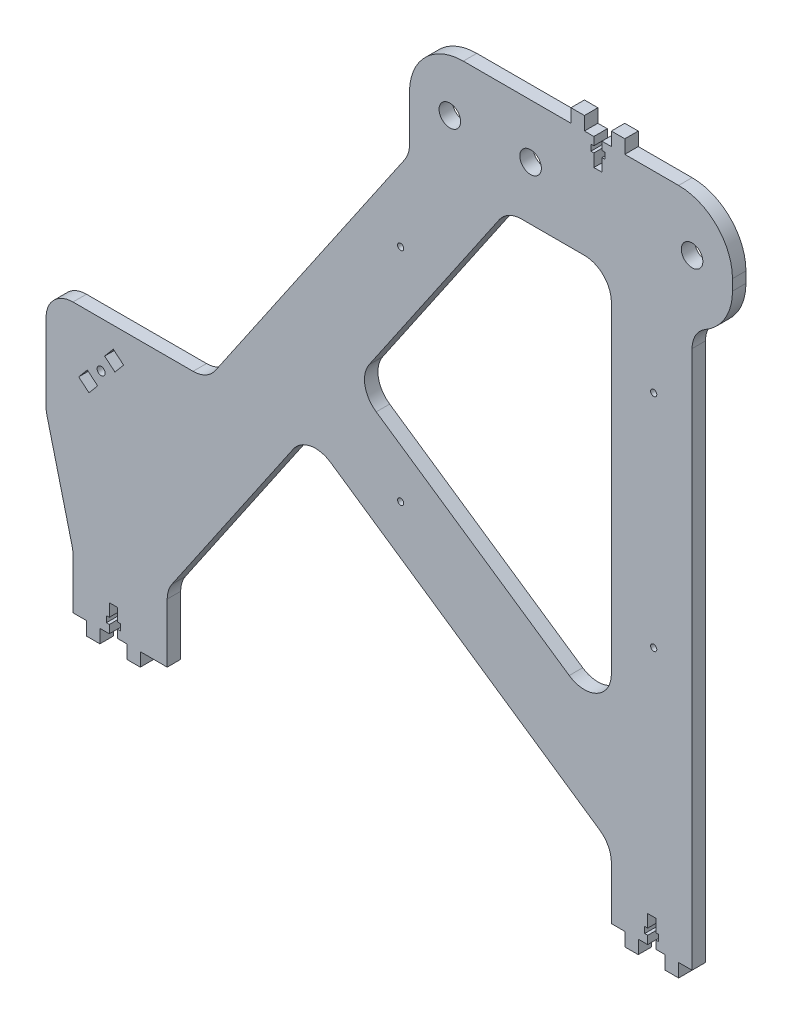
SolidWorks part; units mm, degrees
ref_plane "Plan de face" through (0, 0, 0) normal (0, 0, 1) x (1, 0, 0)
ref_plane "Plan de dessus" through (0, 0, 0) normal (0, 1, 0) x (1, 0, 0)
ref_plane "Plan de droite" through (0, 0, 0) normal (1, 0, 0) x (0, 0, -1)
sketch "Esquisse1" plane through (0, 0, 0) normal (0, 0, 1) x (1, 0, 0)
  line L0 (0, 0) -> (0, 38.8315) construction
  line L1 (-35, 0) -> (220.1536, 0) construction
  line L2 (-20, 0) -> (-20, 33.6786) construction
  line L3 (-21.5, 0) -> (-25, 0)
  line L4 (-25, -5) -> (-30, -5)
  line L5 (-30, -5) -> (-30, 0)
  line L6 (-25, -5) -> (-25, 0)
  line L7 (-18.5, 0) -> (-15, 0)
  line L8 (-15, 0) -> (-15, -5)
  line L9 (-15, -5) -> (-10, -5)
  line L10 (-10, -5) -> (-10, 0)
  line L11 (-21.5, 0) -> (-18.5, 0) construction
  line L12 (-18.5, 0) -> (-18.5, 3)
  line L13 (-18.5, 5.3) -> (-17.4, 5.3)
  line L14 (-22.6, 3) -> (-22.6, 5.3)
  line L15 (-17.4, 3) -> (-18.5, 3)
  line L16 (-18.5, 5.3) -> (-18.5, 10)
  line L17 (-18.5, 10) -> (-21.5, 10)
  line L18 (-21.5, 10) -> (-21.5, 5.3)
  line L19 (-21.5, 3) -> (-22.6, 3)
  line L20 (-17.4, 5.3) -> (-17.4, 3)
  line L21 (-22.6, 5.3) -> (-21.5, 5.3)
  line L22 (-21.5, 3) -> (-21.5, 0)
  line L23 (-20, 10) -> (-20, 0) construction
  line L45 (0, 0) -> (0, 95.9934) construction
  line L47 (-35, 95.9934) -> (-35, 0) construction
  line L48 (-35, 0) -> (-30, 0)
  line L52 (0, 20) -> (-35, 20) construction
  line L55 (-35, 20) -> (-57.9813, 39.2836) construction
  line L56 (-57.9813, 39.2836) -> (9.2875, 119.4515) construction
  line L57 (-35, 20) -> (-54.2836, 42.9813) construction
  line L58 (-54.2836, 42.9813) -> (25.8842, 110.2501) construction
  line L59 (-35, 20) -> (-50, 45.9808) construction
  line L60 (-50, 45.9808) -> (40.631, 98.3066) construction
  line L61 (-35, 20) -> (-45.2606, 48.1908) construction
  line L62 (-45.2606, 48.1908) -> (53.0798, 83.9838) construction
  line L63 (-45, 100) -> (14.8866, 100)
  line L65 (-45, 100) -> (-45, 60)
  line L66 (-45, 60) -> (-35, 20)
  line L67 (-35, 20) -> (-35, 0)
  line L68 (117.314, 250) -> (14.8866, 100) construction
  line L71 (86.7293, 178.6106) -> (180.7293, 178.6106) construction
  line L72 (117.314, 250) -> (210, 250) construction
  line L73 (210, 250) -> (210, 210)
  line L75 (135, 230) -> (210, 230) construction
  line L77 (14.8866, 100) -> (90, 210)
  line L79 (90, 210) -> (90, 250)
  line L80 (90, 250) -> (117.314, 250)
  line L81 (135, 230) -> (105, 230) construction
  line L82 (170, 250) -> (210, 250)
  line L83 (150, 250) -> (117.314, 250)
  line L84 (160, 250) -> (160, 238.7792) construction
  line L85 (161.5, 250) -> (165, 250)
  line L86 (165, 255) -> (170, 255)
  line L87 (170, 255) -> (170, 250)
  line L88 (165, 255) -> (165, 250)
  line L89 (158.5, 250) -> (155, 250)
  line L90 (155, 250) -> (155, 255)
  line L91 (155, 255) -> (150, 255)
  line L92 (150, 255) -> (150, 250)
  line L93 (161.5, 250) -> (158.5, 250) construction
  line L94 (158.5, 250) -> (158.5, 247)
  line L95 (158.5, 244.7) -> (157.4, 244.7)
  line L96 (162.6, 247) -> (162.6, 244.7)
  line L97 (157.4, 247) -> (158.5, 247)
  line L98 (158.5, 244.7) -> (158.5, 240)
  line L99 (158.5, 240) -> (161.5, 240)
  line L100 (161.5, 240) -> (161.5, 244.7)
  line L101 (161.5, 247) -> (162.6, 247)
  line L102 (157.4, 244.7) -> (157.4, 247)
  line L103 (162.6, 244.7) -> (161.5, 244.7)
  line L104 (161.5, 247) -> (161.5, 250)
  line L105 (160, 240) -> (160, 250) construction
  line L106 (-10, 0) -> (0, 0)
  line L107 (190, 0) -> (195, 0)
  line L108 (195, 0) -> (195, 210)
  line L109 (195, 210) -> (210, 210)
  line L110 (170, 0) -> (165, 0)
  line L112 (180, 0) -> (180, 11.2208) construction
  line L113 (178.5, 0) -> (175, 0)
  line L114 (175, -5) -> (170, -5)
  line L115 (170, -5) -> (170, 0)
  line L116 (175, -5) -> (175, 0)
  line L117 (181.5, 0) -> (185, 0)
  line L118 (185, 0) -> (185, -5)
  line L119 (185, -5) -> (190, -5)
  line L120 (190, -5) -> (190, 0)
  line L121 (178.5, 0) -> (181.5, 0) construction
  line L122 (181.5, 0) -> (181.5, 3)
  line L123 (181.5, 5.3) -> (182.6, 5.3)
  line L124 (177.4, 3) -> (177.4, 5.3)
  line L125 (182.6, 3) -> (181.5, 3)
  line L126 (181.5, 5.3) -> (181.5, 10)
  line L127 (181.5, 10) -> (178.5, 10)
  line L128 (178.5, 10) -> (178.5, 5.3)
  line L129 (178.5, 3) -> (177.4, 3)
  line L130 (182.6, 5.3) -> (182.6, 3)
  line L131 (177.4, 5.3) -> (178.5, 5.3)
  line L132 (178.5, 3) -> (178.5, 0)
  line L133 (180, 10) -> (180, 0) construction
  line L134 (165, 0) -> (165, 210) construction
  line L135 (165, 210) -> (126.327, 210)
  line L136 (126.327, 210) -> (0, 25) construction
  line L137 (0, 25) -> (0, 0)
  line L138 (180.7293, 178.6106) -> (180.7293, 96.6106) construction
  line L139 (180.7293, 96.6106) -> (86.7293, 96.6106) construction
  line L140 (86.7293, 96.6106) -> (86.7293, 178.6106) construction
  line L141 (0, 25) -> (52.4705, 101.8406)
  line L142 (52.4705, 101.8406) -> (165, 25)
  line L143 (165, 25) -> (165, 0)
  line L144 (69.3881, 126.6156) -> (165, 61.327)
  line L145 (165, 61.327) -> (165, 210)
  line L146 (126.327, 210) -> (69.3881, 126.6156)
  line L147 (66.4529, 175.5164) -> (91.2278, 158.5988) construction
  line L148 (78.8404, 167.0576) -> (37.9736, 107.2102) construction
  line L149 (64.949, 93.3197) -> (81.8665, 118.0947) construction
  line L150 (73.4078, 105.7072) -> (48.5418, 122.6869) construction
  circle A7 centre (135, 230) radius 4
  circle A8 centre (195, 230) radius 4
  circle A9 centre (105, 230) radius 4
  circle A10 centre (86.7293, 178.6106) radius 1.15
  circle A11 centre (180.7293, 96.6106) radius 1.15
  circle A12 centre (86.7293, 96.6106) radius 1.15
  circle A13 centre (180.7293, 178.6106) radius 1.15
  point P68 (-35, 20)
  point P86 (90, 230)
  line B0 (-29.6722, 80.7998) -> (-32.8861, 76.9696)
  line B1 (-29.6722, 80.7998) -> (-25.842, 77.5859)
  line B2 (-25.842, 77.5859) -> (-29.0559, 73.7556)
  line B3 (-32.8861, 76.9696) -> (-29.0559, 73.7556)
  line B4 (-23.2443, 88.4602) -> (-20.0304, 92.2905)
  line B5 (-23.2443, 88.4602) -> (-19.4141, 85.2463)
  line B6 (-19.4141, 85.2463) -> (-16.2001, 89.0765)
  line B7 (-20.0304, 92.2905) -> (-16.2001, 89.0765)
  line B8 (-24.5431, 83.023) -> (-29.8843, 87.5048) construction
  circle B9 centre (-24.5431, 83.023) radius 1.5
  dimension "D14" = 100
  dimension "D25" = 8
  dimension "D52" = 2.3
  dimension "D1" = 20
  dimension "D2" = 10
  dimension "D3" = 5
  dimension "D4" = 5
  dimension "D5" = 5.2
  dimension "D6" = 3
  dimension "D7" = 2.3
  dimension "D8" = 3
  dimension "D9" = 10
  dimension "D10" = 5
  dimension "D11" = 200
  dimension "D12" = 10
  dimension "D13" = 20
  dimension "D15" = 15
  dimension "D16" = 30
  dimension "D17" = 50
  dimension "D18" = 55
  dimension "D20" = 10
  dimension "D21" = 40
  dimension "D22" = 230
  dimension "D23" = 5
  dimension "D24" = 30
  dimension "D26" = 60
  dimension "D27" = 15
  dimension "D28" = 40
  dimension "D29" = 30
  dimension "D30" = 15
  dimension "D31" = 25
  dimension "D32" = 10
  dimension "D33" = 5
  dimension "D34" = 5
  dimension "D35" = 5.2
  dimension "D36" = 3
  dimension "D37" = 2.3
  dimension "D38" = 3
  dimension "D39" = 10
  dimension "D40" = 10
  dimension "D41" = 5
  dimension "D42" = 5
  dimension "D43" = 5.2
  dimension "D44" = 3
  dimension "D45" = 2.3
  dimension "D46" = 3
  dimension "D47" = 10
  dimension "D48" = 30
  dimension "D49" = 25
  dimension "D50" = 94
  dimension "D51" = 82
  dimension "D19" = 4
sketch_block_instance "Trou M3 plots 5mm-1"
sketch_block "Trou M3 plots 5mm" parameters "D2"=3, "D1"=5, "D3"=5, "D4"=10
sketch_block_instance "Trou M3 plots 5mm-6"
sketch_block_instance "Trou M3 plots 5mm-7"
sketch_block_instance "Trou M3 plots 5mm-8"
extrude "Boss.-Extru.1" add sketch "Esquisse1" along normal blind 5
fillet "Congé1" radius 10 13 edges at (-35, 20, 2.5) (-45, 60, 2.5) (195, 210, 2.5) (90, 210, 2.5) (-45, 100, 2.5) (14.8866, 100, 2.5) (0, 25, 2.5) (165, 25, 2.5) (165, 61.327, 2.5) (52.4705, 101.8406, 2.5) (69.3881, 126.6156, 2.5) (126.327, 210, 2.5) (165, 210, 2.5)
fillet "Congé2" radius 20 3 edges at (90, 250, 2.5) (210, 250, 2.5) (210, 210, 2.5)
